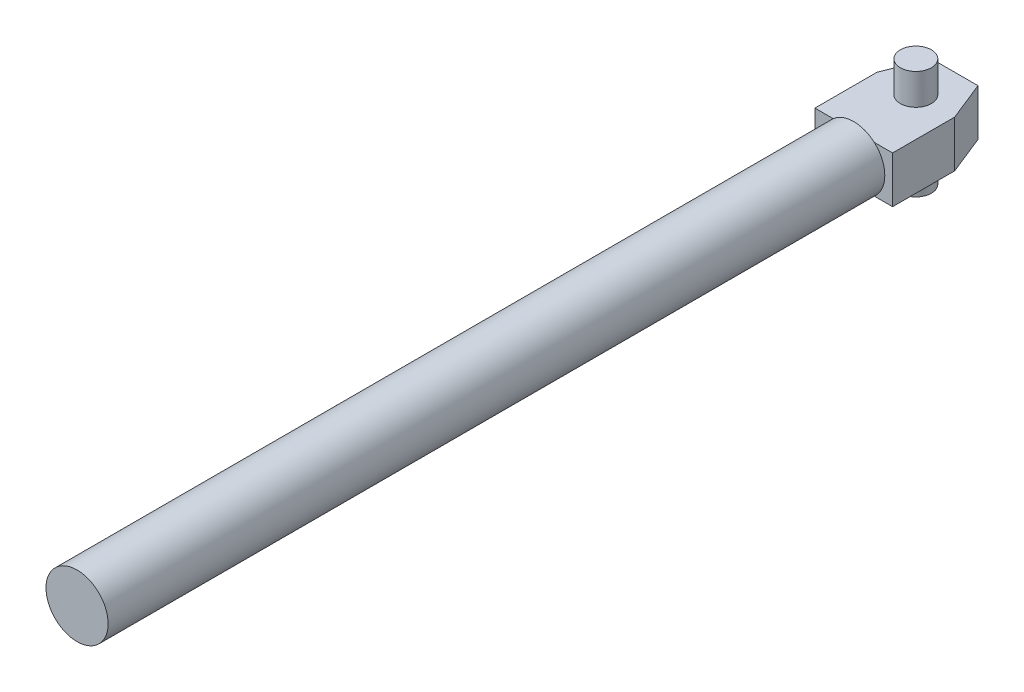
SolidWorks part; units mm, degrees
ref_plane "Front Plane" through (0, 0, 0) normal (0, 0, 1) x (1, 0, 0)
ref_plane "Top Plane" through (0, 0, 0) normal (0, 1, 0) x (1, 0, 0)
ref_plane "Right Plane" through (0, 0, 0) normal (1, 0, 0) x (0, 0, -1)
sketch "Sketch1" plane through (0, 0, 0) normal (0, 0, 1) x (1, 0, 0)
  circle A0 centre (0, 0) radius 20
  dimension "D1" = 40
extrude "Boss-Extrude1" add sketch "Sketch1" along normal blind 500
sketch "Sketch2" plane through (0, 0, 0) normal (0, 1, 0) x (1, 0, 0)
  line L0 (0, 65) -> (0, 0) construction
  line L1 (-25, 0) -> (25, 0)
  line L2 (-25, 0) -> (-25, 40)
  line L3 (-15, 65) -> (15, 65)
  line L4 (25, 0) -> (25, 40)
  line L5 (15, 65) -> (25, 40)
  line L6 (-25, 40) -> (-15, 65)
  line L7 (20, 0) -> (-20, 0) construction
  point P1 (25, 65)
  point P2 (-25, 65)
  dimension "D1" = 50
  dimension "D2" = 10
  dimension "D3" = 25
  dimension "D4" = 25
  dimension "D5" = 10
  dimension "D6" = 65
extrude "Boss-Extrude2" add sketch "Sketch2" along normal mid plane 30
sketch "Sketch3" plane through (0, 0, 0) normal (0, 1, 0) x (1, 0, 0)
  circle A0 centre (0, 40) radius 10
  dimension "D1" = 20
  dimension "D2" = 40
extrude "Boss-Extrude3" add sketch "Sketch3" along normal blind 35 and the other way blind 35
